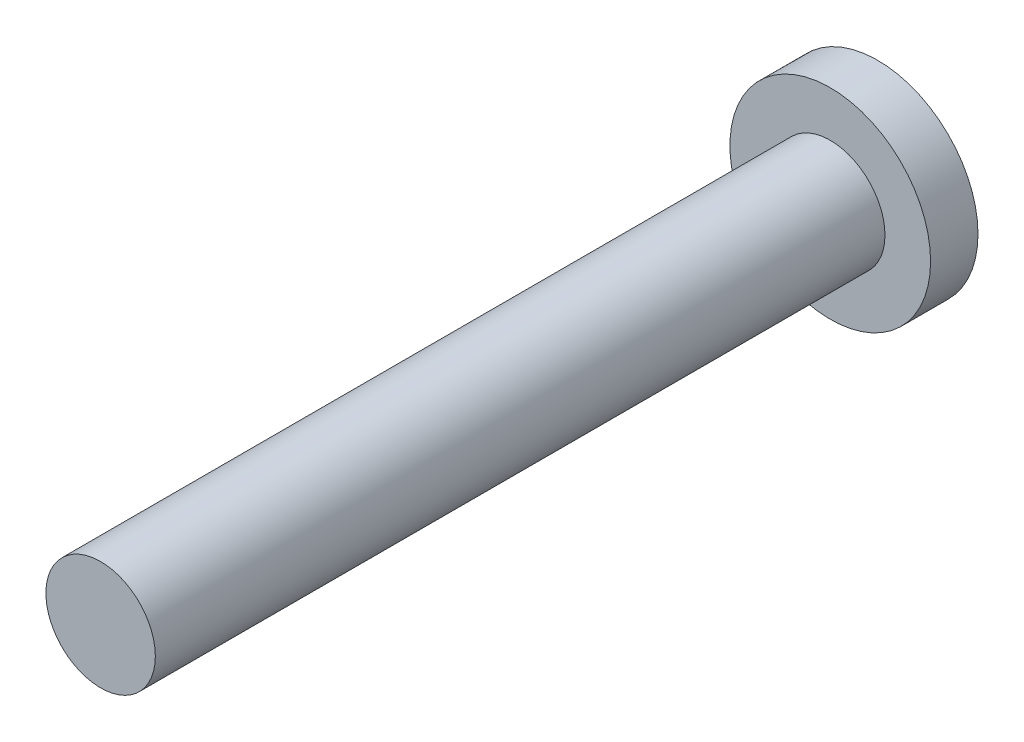
SolidWorks part; units mm, degrees
ref_plane "Plan de face" through (0, 0, 0) normal (0, 0, 1) x (1, 0, 0)
ref_plane "Plan de dessus" through (0, 0, 0) normal (0, 1, 0) x (1, 0, 0)
ref_plane "Plan de droite" through (0, 0, 0) normal (1, 0, 0) x (0, 0, -1)
sketch "Esquisse1" plane through (0, 0, 0) normal (0, 0, 1) x (1, 0, 0)
  circle A0 centre (0, 0) radius 1.5
  dimension "D1" = 3
extrude "Boss.-Extru.1" add sketch "Esquisse1" along normal blind 20
cosmetic thread "Représentation de filetage1" parameters "D1"=18, "D2"=2.439
sketch "Esquisse2" plane through (0, 0, 0) normal (0, 0, 1) x (1, 0, 0)
  circle A0 centre (0, 0) radius 2.75
  dimension "D1" = 5.5
extrude "Boss.-Extru.2" add sketch "Esquisse2" against normal blind 1.3
